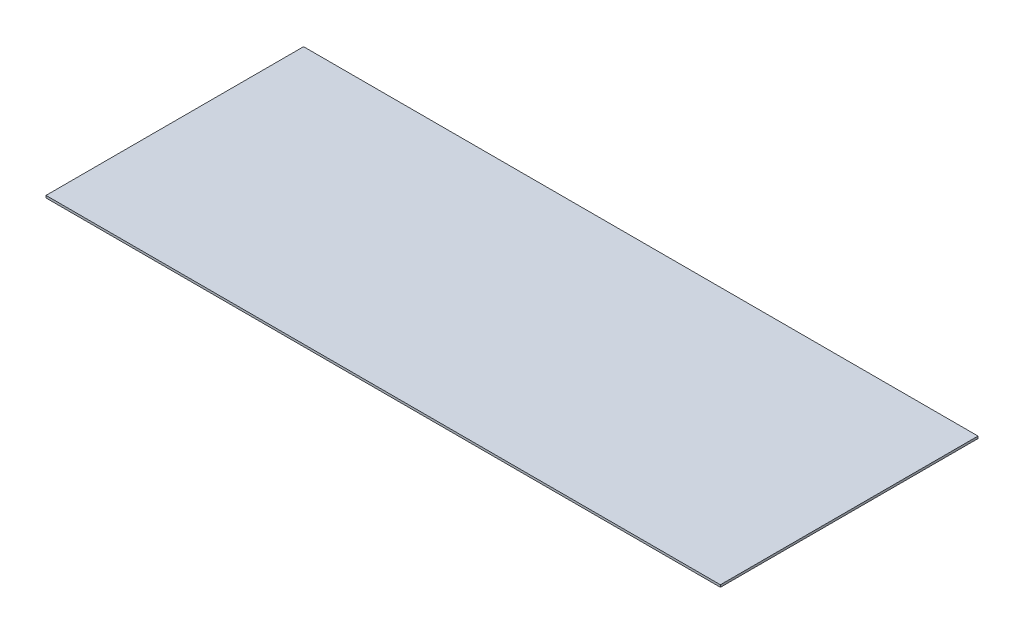
SolidWorks part; units mm, degrees
ref_plane "Front Plane" through (0, 0, 0) normal (0, 0, 1) x (1, 0, 0)
ref_plane "Top Plane" through (0, 0, 0) normal (0, 1, 0) x (1, 0, 0)
ref_plane "Right Plane" through (0, 0, 0) normal (1, 0, 0) x (0, 0, -1)
sketch "Sketch1" plane through (0, 0, 0) normal (0, 1, 0) x (1, 0, 0)
  line L1 (-101.7766, 51.6195) -> (355.4234, 51.6195)
  line L2 (-101.7766, 51.6195) -> (-101.7766, -123.0055)
  line L3 (-101.7766, -123.0055) -> (355.4234, -123.0055)
  line L4 (355.4234, 51.6195) -> (355.4234, -123.0055)
  dimension "D1" = 457.2
  dimension "D2" = 174.625
extrude "Boss-Extrude1" add sketch "Sketch1" against normal blind 1.5189
